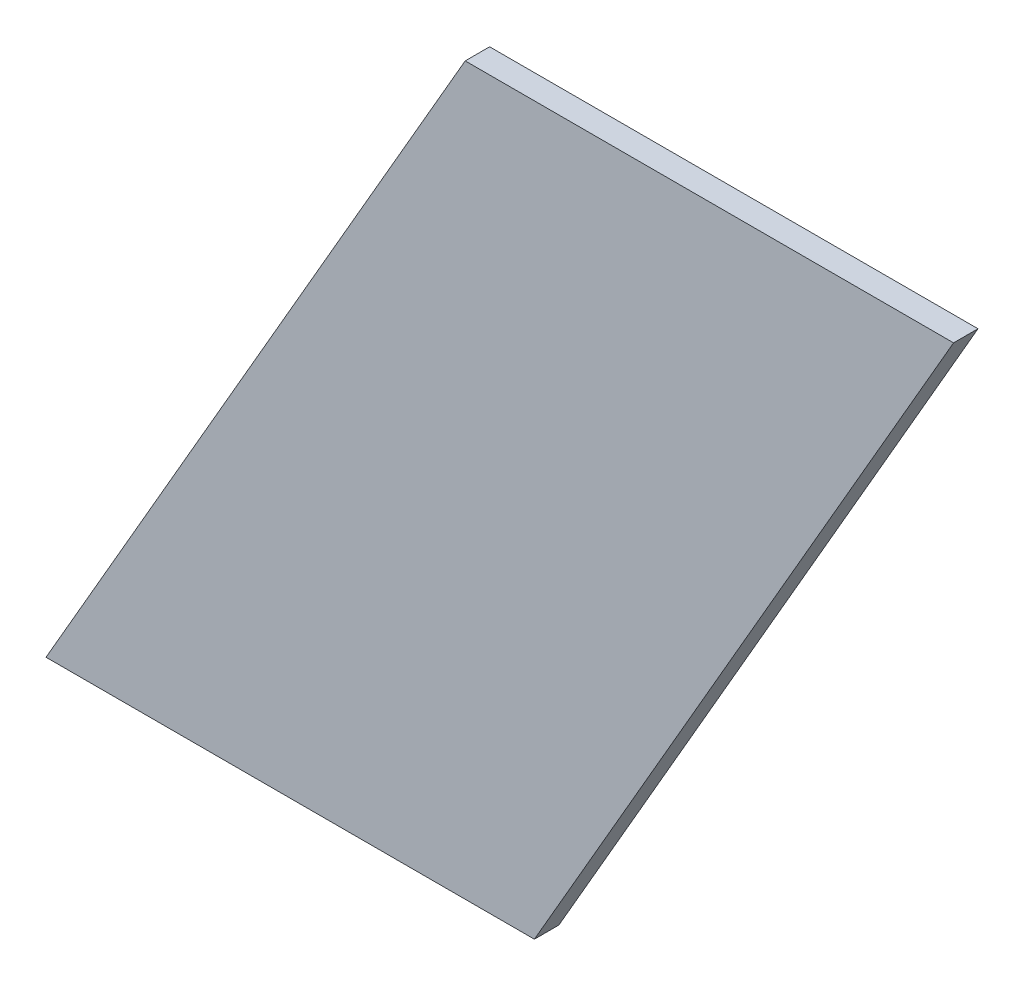
SolidWorks part; units mm, degrees
ref_plane "Front Plane" through (0, 0, 0) normal (0, 0, 1) x (1, 0, 0)
ref_plane "Top Plane" through (0, 0, 0) normal (0, 1, 0) x (1, 0, 0)
ref_plane "Right Plane" through (0, 0, 0) normal (1, 0, 0) x (0, 0, -1)
sketch "Sketch1" plane through (0, 0, 0) normal (0, 0, 1) x (1, 0, 0)
  line L1 (-0.0425, 0.446) -> (0.5575, 0.446)
  line L2 (-0.0425, 0.446) -> (-0.5575, -0.446)
  line L3 (-0.5575, -0.446) -> (0.0425, -0.446)
  line L4 (0.5575, 0.446) -> (0.0425, -0.446)
  line L5 (-0.0425, 0.446) -> (0.0425, -0.446) construction
  line L6 (-0.5575, -0.446) -> (0.5575, 0.446) construction
  point P0 (0, 0)
  point P5 (0, 0)
  point P6 (7.62, 20.3481)
  point P8 (0, 0)
  dimension "D1" = 1.03
  dimension "D2" = 0.6
  dimension "D3" = 60
extrude "Boss-Extrude2" add sketch "Sketch1" along normal mid plane 0.03
